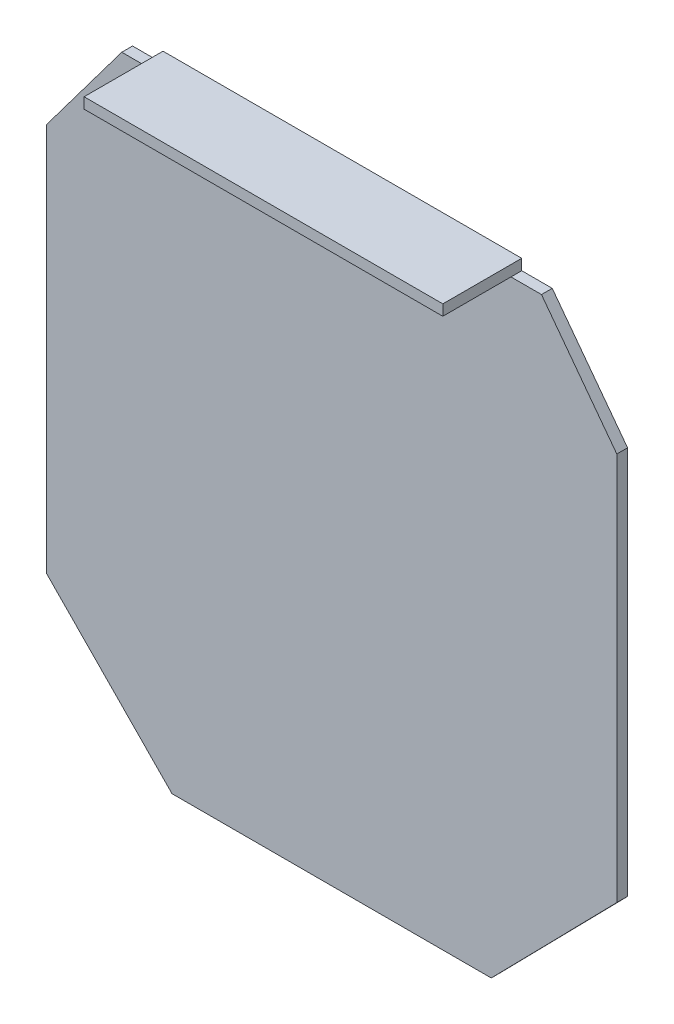
SolidWorks part; units mm, degrees
ref_plane "Спереди" through (0, 0, 0) normal (0, 0, 1) x (1, 0, 0)
ref_plane "Сверху" through (0, 0, 0) normal (0, 1, 0) x (1, 0, 0)
ref_plane "Справа" through (0, 0, 0) normal (1, 0, 0) x (0, 0, -1)
sketch "Sketch1" plane through (0, 0, 0) normal (0, 0, 1) x (1, 0, 0)
  line L0 (-79.5, 58) -> (-79.5, -50.2929)
  line L1 (-79.5, -50.2929) -> (-44.5, -86)
  line L2 (-44.5, -86) -> (44.5, -86)
  line L3 (44.5, -86) -> (79.5, -50.2929)
  line L4 (79.5, -50.2929) -> (79.5, 58)
  line L5 (79.5, 58) -> (58.5, 86)
  line L6 (58.5, 86) -> (-58.5, 86)
  line L7 (-58.5, 86) -> (-79.5, 58)
  line L8 (0, 86) -> (0, -86) construction
  point P7 (0, 0)
  dimension "D1" = 172
  dimension "D2" = 159
  dimension "D3" = 50
  dimension "D4" = 50
  dimension "D5" = 35
  dimension "D6" = 35
  dimension "D7" = 35
  dimension "D8" = 35
  dimension "D9" = 28
  dimension "D10" = 28
extrude "Boss-Extrude1" add sketch "Sketch1" along normal blind 3
sketch "Sketch3" plane through (0, 86, 0) normal (0, 1, 0) x (1, 0, 0)
  line L0 (0, 0) -> (0, -44.8705) construction
  line L1 (58.5, 0) -> (-58.5, 0) construction
  line L2 (-50, -22) -> (50, -22)
  line L3 (-50, -22) -> (-50, 0)
  line L4 (-50, 0) -> (50, 0)
  line L5 (50, -22) -> (50, 0)
  line L6 (-50, -22) -> (50, 0) construction
  line L7 (-50, 0) -> (50, -22) construction
  point P3 (0, -11)
  dimension "D1" = 100
  dimension "D2" = 22
extrude "Boss-Extrude2" add sketch "Sketch3" along normal blind 3
